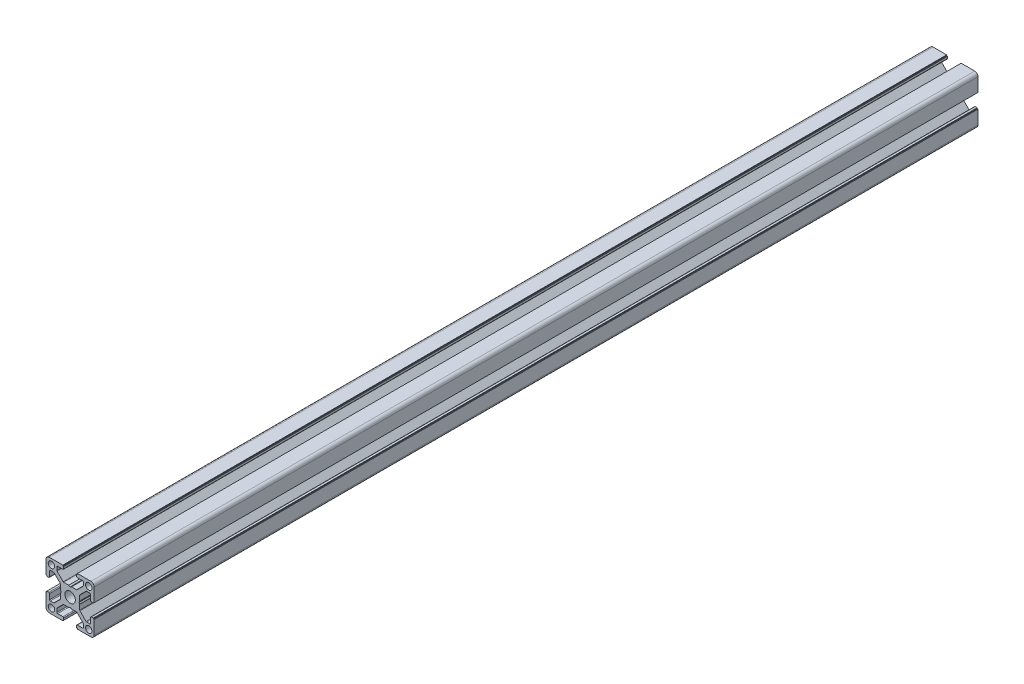
SolidWorks part; units mm, degrees
ref_plane "Front Plane" through (0, 0, 0) normal (0, 0, 1) x (1, 0, 0)
ref_plane "Top Plane" through (0, 0, 0) normal (0, 1, 0) x (1, 0, 0)
ref_plane "Right Plane" through (0, 0, 0) normal (1, 0, 0) x (0, 0, -1)
sketch "Sketch1" plane through (0, 0, 0) normal (0, 0, 1) x (1, 0, 0)
  line L0 (-15, 0) -> (15, 0) construction
  line L1 (0, -15) -> (0, 15) construction
  line L2 (-4.5, 15) -> (4.5, 15) construction
  line L3 (-4, -15) -> (4, -15) construction
  line L4 (-4.5, 15) -> (-4.5, 14.5)
  line L5 (-4.5, 14.5) -> (-4, 14.5)
  line L6 (-4, 14.5) -> (-4, 13.29)
  line L7 (-4.5, 12.79) -> (-7.7675, 12.79)
  line L8 (-8.2675, 12.29) -> (-8.2675, 10.2707)
  line L9 (-8.1211, 9.9171) -> (-4.3504, 6.1464)
  line L10 (-3.9968, 6) -> (0, 6)
  line L11 (0, 0) -> (-15, 15) construction
  line L12 (-4.5, 15) -> (-12.968, 15)
  line L14 (-12.705, 9.5135) -> (-10.5135, 9.5135) construction
  line L15 (-13.705, 10.5135) -> (-13.705, 12.705) construction
  line L16 (-12.705, 13.705) -> (-10.5135, 13.705) construction
  line L17 (-9.5135, 10.5135) -> (-9.5135, 12.705) construction
  line L18 (-13.705, 9.5135) -> (-9.5135, 13.705) construction
  line L19 (-13.705, 13.705) -> (-9.5135, 9.5135) construction
  line L20 (-3.1568, 4.5038) -> (-1.318, 2.9707) construction
  line L21 (-4.5038, 3.1568) -> (-2.9707, 1.318) construction
  line L22 (-6, 3.9968) -> (-6, 0)
  line L23 (-9.9171, 8.1211) -> (-6.1464, 4.3504)
  line L24 (-15, 4.5) -> (-15, 12.968)
  line L25 (-12.29, 8.2675) -> (-10.2707, 8.2675)
  line L26 (-12.79, 4.5) -> (-12.79, 7.7675)
  line L27 (-14.5, 4) -> (-13.29, 4)
  line L28 (-14.5, 4.5) -> (-14.5, 4)
  line L29 (-15, 4.5) -> (-14.5, 4.5)
  circle A0 centre (0, 0) radius 3.25
  arc A1 (-12.968, 15) -> (-15, 12.968) centre (-12.968, 12.968) ccw
  circle A2 centre (0, 0) radius 5.5 construction
  arc A3 (-10.5135, 9.5135) -> (-9.5135, 10.5135) centre (-10.5135, 10.5135) ccw construction
  arc A4 (-13.705, 12.705) -> (-12.705, 13.705) centre (-12.705, 12.705) cw construction
  arc A5 (-10.5135, 13.705) -> (-9.5135, 12.705) centre (-10.5135, 12.705) cw construction
  arc A6 (-12.705, 9.5135) -> (-13.705, 10.5135) centre (-12.705, 10.5135) cw construction
  arc A7 (-12.79, 4.5) -> (-13.29, 4) centre (-13.29, 4.5) cw
  arc A8 (-12.29, 8.2675) -> (-12.79, 7.7675) centre (-12.29, 7.7675) ccw
  arc A9 (-9.9171, 8.1211) -> (-10.2707, 8.2675) centre (-10.2707, 7.7675) ccw
  arc A10 (-6, 3.9968) -> (-6.1464, 4.3504) centre (-6.5, 3.9968) ccw
  arc A11 (-4.3504, 6.1464) -> (-3.9968, 6) centre (-3.9968, 6.5) ccw
  arc A12 (-4, 13.29) -> (-4.5, 12.79) centre (-4.5, 13.29) cw
  arc A13 (-7.7675, 12.79) -> (-8.2675, 12.29) centre (-7.7675, 12.29) ccw
  arc A14 (-8.2675, 10.2707) -> (-8.1211, 9.9171) centre (-7.7675, 10.2707) ccw
  circle A15 centre (-11.6092, 11.6093) radius 2
  point P4 (0, 0)
  point P8 (0, 0)
  point P13 (0, 15)
  point P15 (0, -15)
  point P16 (0, 6)
  point P23 (-11.6092, 11.6093)
  point P26 (0, 6)
  point P62 (-12.79, 4)
  point P65 (-12.79, 8.2675)
  point P68 (-10.0636, 8.2675)
  point P71 (-6, 4.2039)
  point P74 (-4.2039, 6)
  point P77 (-4, 12.79)
  point P80 (-8.2675, 12.79)
  point P83 (-8.2675, 10.0636)
  dimension "Center Hole Diameter" = 6.5
  dimension "D11" = 2.032
  dimension "D9" = 11
  dimension "D13" = 1
  dimension "D14" = 0.5
  dimension "D15" = 4
  dimension "Rail Height" = 30
  dimension "Rail Width" = 30
  dimension "T-Slot Width" = 8
  dimension "T-Slot Depth" = 9
  dimension "D1" = 9
  dimension "D2" = 45
  dimension "D3" = 8
  dimension "D4" = 2.21
  dimension "D5" = 16.535
  dimension "D7" = 2.54
  dimension "D6" = 1.295
  dimension "D8" = 1.246
  dimension "D10" = 10.36
  dimension "D12" = 1.905
sketch "Sketch2" plane through (0, 0, 0) normal (1, 0, 0) x (0, 0, -1)
  line L0 (-304.8, 0) -> (304.8, 0) construction
  line L2 (0, -15) -> (0, 15) construction
  line L3 (0, -15) -> (0, 15) construction
  line L4 (-304.8, -15) -> (-304.8, 15) construction
  line L5 (304.8, -15) -> (304.8, 15) construction
  point P0 (-267.3, 0)
  point P3 (0, 0)
  point P4 (267.3, 0)
  point P12 (-304.8, 0)
  point P14 (304.8, 0)
  dimension "Length" = 609.6
  dimension "D1" = 37.5
sketch "Sketch3" plane through (0, 0, 0) normal (0, 0, 1) x (1, 0, 0)
  line L0 (-4.5038, 3.1568) -> (-2.9707, 1.318) construction
  line L1 (0, 3.25) -> (0, 5.5)
  line L2 (-5.5, 0) -> (-3.25, 0)
  line L3 (-11.6092, 13.705) -> (-11.6092, 9.5135) construction
  line L7 (-6, 3.9968) -> (-6, 0) construction
  line L31 (-9.9171, 8.1211) -> (-6.1464, 4.3504) construction
  line L117 (-12.29, 8.2675) -> (-10.2707, 8.2675) construction
  line L118 (-12.79, 4.5) -> (-12.79, 7.7675) construction
  line L157 (-12.705, 9.5135) -> (-10.5135, 9.5135)
  line L158 (-9.5135, 10.5135) -> (-9.5135, 12.705)
  line L163 (-10.5135, 13.705) -> (-12.705, 13.705)
  line L164 (-13.705, 12.705) -> (-13.705, 10.5135)
  line L165 (-12.705, 9.5135) -> (-10.5135, 9.5135) construction
  line L166 (-9.5135, 10.5135) -> (-9.5135, 12.705) construction
  line L167 (-10.5135, 13.705) -> (-12.705, 13.705) construction
  line L168 (-13.705, 12.705) -> (-13.705, 10.5135) construction
  line L169 (-14.5, 4) -> (-13.29, 4) construction
  line L170 (-14.5, 4.5) -> (-14.5, 4) construction
  line L171 (-15, 4.5) -> (-14.5, 4.5) construction
  line L172 (-15, 4.5) -> (-15, 12.968) construction
  line L173 (-4.5, 15) -> (-12.968, 15) construction
  line L174 (-4.5, 15) -> (-4.5, 14.5) construction
  line L175 (-4.5, 14.5) -> (-4, 14.5) construction
  line L176 (-4, 14.5) -> (-4, 13.29) construction
  line L177 (-4.5, 12.79) -> (-7.7675, 12.79) construction
  line L178 (-8.2675, 12.29) -> (-8.2675, 10.2707) construction
  line L179 (-8.1211, 9.9171) -> (-4.3504, 6.1464) construction
  line L180 (-3.9968, 6) -> (0, 6) construction
  line L181 (-6, 3.9968) -> (-6, 0.866)
  line L182 (-9.9171, 8.1211) -> (-6.1464, 4.3504)
  line L183 (-12.29, 8.2675) -> (-10.2707, 8.2675)
  line L184 (-12.79, 4.5) -> (-12.79, 7.7675)
  line L185 (-14.5, 4) -> (-13.29, 4)
  line L186 (-14.5, 4.5) -> (-14.5, 4)
  line L187 (-15, 4.5) -> (-14.5, 4.5)
  line L188 (-15, 4.5) -> (-15, 12.968)
  line L189 (-4.5, 15) -> (-12.968, 15)
  line L190 (-4.5, 15) -> (-4.5, 14.5)
  line L191 (-4.5, 14.5) -> (-4, 14.5)
  line L192 (-4, 14.5) -> (-4, 13.29)
  line L193 (-4.5, 12.79) -> (-7.7675, 12.79)
  line L194 (-8.2675, 12.29) -> (-8.2675, 10.2707)
  line L195 (-8.1211, 9.9171) -> (-4.3504, 6.1464)
  line L196 (-3.9968, 6) -> (-0.866, 6)
  line L197 (-0.866, 6) -> (0, 5.5)
  line L198 (0, -15) -> (0, 15) construction
  line L199 (0, 0) -> (-15, 15) construction
  line L200 (0, 0) -> (-15, 15) construction
  line L201 (-3.1568, 4.5038) -> (-1.318, 2.9707) construction
  line L202 (-3.1568, 4.5038) -> (-1.318, 2.9707) construction
  line L203 (-6, 0.866) -> (-5.5, 0)
  line L204 (-15, 0) -> (15, 0) construction
  line L205 (-15, 0) -> (15, 0) construction
  line L206 (0, -15) -> (0, 15) construction
  arc A0 (-3.25, 0) -> (-2.9707, 1.318) centre (0, 0) cw
  arc A1 (-2.9707, 1.318) -> (-1.318, 2.9707) centre (0, 0) cw
  arc A10 (-6, 3.9968) -> (-6.1464, 4.3504) centre (-6.5, 3.9968) ccw construction
  circle A13 centre (-11.6092, 11.6093) radius 2
  circle A16 centre (0, 0) radius 3.25
  arc A18 (0, 3.25) -> (-1.318, 2.9707) centre (0, 0) ccw
  arc A20 (-9.9171, 8.1211) -> (-10.2707, 8.2675) centre (-10.2707, 7.7675) ccw construction
  arc A22 (-12.29, 8.2675) -> (-12.79, 7.7675) centre (-12.29, 7.7675) ccw construction
  arc A28 (-13.29, 4) -> (-12.79, 4.5) centre (-13.29, 4.5) ccw construction
  arc A29 (-10.5135, 9.5135) -> (-9.5135, 10.5135) centre (-10.5135, 10.5135) ccw
  arc A30 (-9.5135, 12.705) -> (-10.5135, 13.705) centre (-10.5135, 12.705) ccw
  arc A31 (-12.705, 13.705) -> (-13.705, 12.705) centre (-12.705, 12.705) ccw
  arc A32 (-13.705, 10.5135) -> (-12.705, 9.5135) centre (-12.705, 10.5135) ccw
  arc A33 (-10.5135, 9.5135) -> (-9.5135, 10.5135) centre (-10.5135, 10.5135) ccw construction
  arc A34 (-9.5135, 12.705) -> (-10.5135, 13.705) centre (-10.5135, 12.705) ccw construction
  arc A35 (-12.705, 13.705) -> (-13.705, 12.705) centre (-12.705, 12.705) ccw construction
  arc A36 (-13.705, 10.5135) -> (-12.705, 9.5135) centre (-12.705, 10.5135) ccw construction
  arc A37 (-12.968, 15) -> (-15, 12.968) centre (-12.968, 12.968) ccw construction
  arc A38 (-4.5, 12.79) -> (-4, 13.29) centre (-4.5, 13.29) ccw construction
  arc A39 (-7.7675, 12.79) -> (-8.2675, 12.29) centre (-7.7675, 12.29) ccw construction
  arc A40 (-8.2675, 10.2707) -> (-8.1211, 9.9171) centre (-7.7675, 10.2707) ccw construction
  arc A41 (-4.3504, 6.1464) -> (-3.9968, 6) centre (-3.9968, 6.5) ccw construction
  arc A42 (-6, 3.9968) -> (-6.1464, 4.3504) centre (-6.5, 3.9968) ccw
  arc A43 (-9.9171, 8.1211) -> (-10.2707, 8.2675) centre (-10.2707, 7.7675) ccw
  arc A44 (-12.29, 8.2675) -> (-12.79, 7.7675) centre (-12.29, 7.7675) ccw
  arc A45 (-13.29, 4) -> (-12.79, 4.5) centre (-13.29, 4.5) ccw
  arc A46 (-12.968, 15) -> (-15, 12.968) centre (-12.968, 12.968) ccw
  arc A47 (-4.5, 12.79) -> (-4, 13.29) centre (-4.5, 13.29) ccw
  arc A48 (-7.7675, 12.79) -> (-8.2675, 12.29) centre (-7.7675, 12.29) ccw
  arc A49 (-8.2675, 10.2707) -> (-8.1211, 9.9171) centre (-7.7675, 10.2707) ccw
  arc A50 (-4.3504, 6.1464) -> (-3.9968, 6) centre (-3.9968, 6.5) ccw
  circle A51 centre (0, 0) radius 5.5 construction
  arc A52 (-3.1568, 4.5038) -> (-4.5038, 3.1568) centre (0, 0) ccw construction
  point P69 (0, 0)
  dimension "D5" = 4
  dimension "D3" = 60
  dimension "D4" = 60
  dimension "D1" = 0
  dimension "D2" = 0
extrude "Boss-Extrude1" add sketch "Sketch3" along normal mid plane 550
pattern_circular "CirPattern1" count 4 over 360 about axis through (0, 0, 0) along (0, 0, 1) of "Boss-Extrude1"
ref_plane "Contact Plane1" through (15, 0, 0) normal (1, 0, 0) x (0, 0, -1)
ref_plane "Contact Plane2" through (0, -15, 0) normal (0, 1, 0) x (1, 0, 0)
ref_plane "Contact Plane3" through (-15, 0, 0) normal (1, 0, 0) x (0, 0, -1)
ref_plane "Contact Plane4" through (0, 15, 0) normal (0, 1, 0) x (1, 0, 0)
equation "\"D1@Sketch2\" = \"Rail Height@Sketch1\" * 1.25"
equation "\"D1@Sketch1\"=\"T-Slot Width@Sketch1\"+1mm"
equation "\"D3@Sketch1\"=\"T-Slot Width@Sketch1\""
equation "\"D1@Boss-Extrude1\"=\"Length@Sketch2\""
